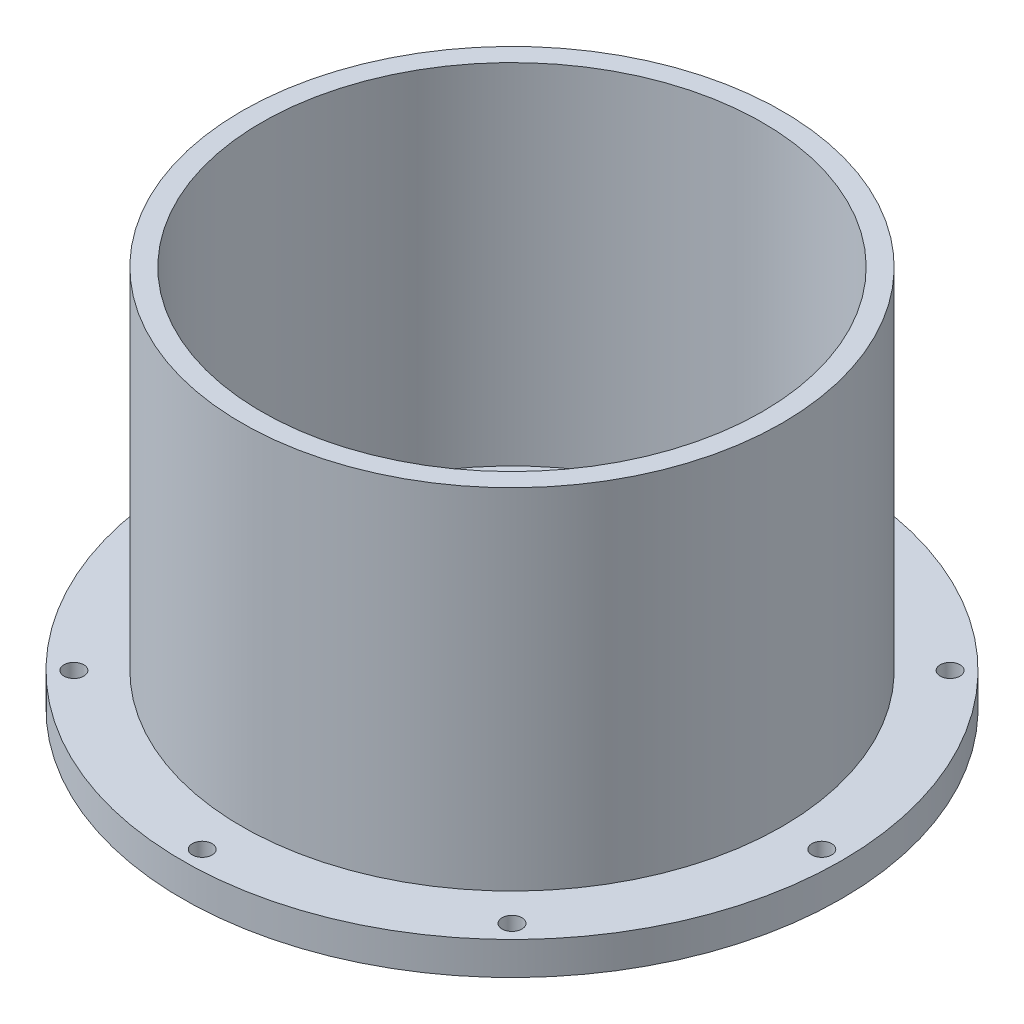
SolidWorks part; units mm, degrees
ref_plane "Front Plane" through (0, 0, 0) normal (0, 0, 1) x (1, 0, 0)
ref_plane "Top Plane" through (0, 0, 0) normal (0, 1, 0) x (1, 0, 0)
ref_plane "Right Plane" through (0, 0, 0) normal (1, 0, 0) x (0, 0, -1)
sketch "Sketch2" plane through (0, 0, 0) normal (0, 0, 1) x (1, 0, 0)
  line L0 (0, 5) -> (0, 0)
  line L1 (0, 0) -> (50, 0)
  line L2 (50, 0) -> (50, 5)
  line L3 (50, 5) -> (41, 5)
  line L4 (41, 5) -> (41, 58)
  line L5 (41, 58) -> (38, 58)
  line L6 (38, 58) -> (38, 5)
  line L7 (38, 5) -> (0, 5)
  line L8 (0, 0) -> (0, 38.6828) construction
  dimension "D1" = 50
  dimension "D2" = 5
  dimension "D3" = 58
  dimension "D4" = 9
  dimension "D5" = 3
revolve "Revolve1" add sketch "Sketch2" angle 360 about L8
sketch "Sketch3" plane through (0, 5, 0) normal (0, 1, 0) x (1, 0, 0)
  line L0 (-13.5, 4) -> (-13.5, -4) construction
  line L1 (13.5, 4) -> (13.5, -4) construction
  line L2 (-13.5, 4) -> (-13.5, 12) construction
  line L3 (0, 0) -> (0, -47) construction
  circle A0 centre (-13.5, 4) radius 1.5
  circle A1 centre (13.5, 4) radius 1.5
  circle A2 centre (-13.5, -4) radius 1.5
  circle A3 centre (-13.5, -12) radius 1.5
  circle A4 centre (13.5, -4) radius 1.5
  circle A5 centre (13.5, -12) radius 1.5
  circle A6 centre (-13.5, 12) radius 1.5
  circle A7 centre (13.5, 12) radius 1.5
  circle A8 centre (0, -47) radius 1.5
  circle A9 centre (0, 0) radius 47 construction
  circle A10 centre (-33.234, -33.234) radius 1.5
  circle A11 centre (-47, 0) radius 1.5
  circle A12 centre (-33.234, 33.234) radius 1.5
  circle A13 centre (0, 47) radius 1.5
  circle A14 centre (33.234, 33.234) radius 1.5
  circle A15 centre (47, 0) radius 1.5
  circle A16 centre (33.234, -33.234) radius 1.5
  dimension "D1" = 3
  dimension "D11" = 3
  dimension "D12" = 94
  dimension "D2" = 27
  dimension "D3" = 13.5
  dimension "D4" = 4
  dimension "D6" = 8
  dimension "D8" = 8
  dimension "D10" = 8
  dimension "D5" = 3
  dimension "D7" = 3
  dimension "D9" = 2
  dimension "D13" = 8
extrude "Cut-Extrude1" cut sketch "Sketch3" against normal through all
